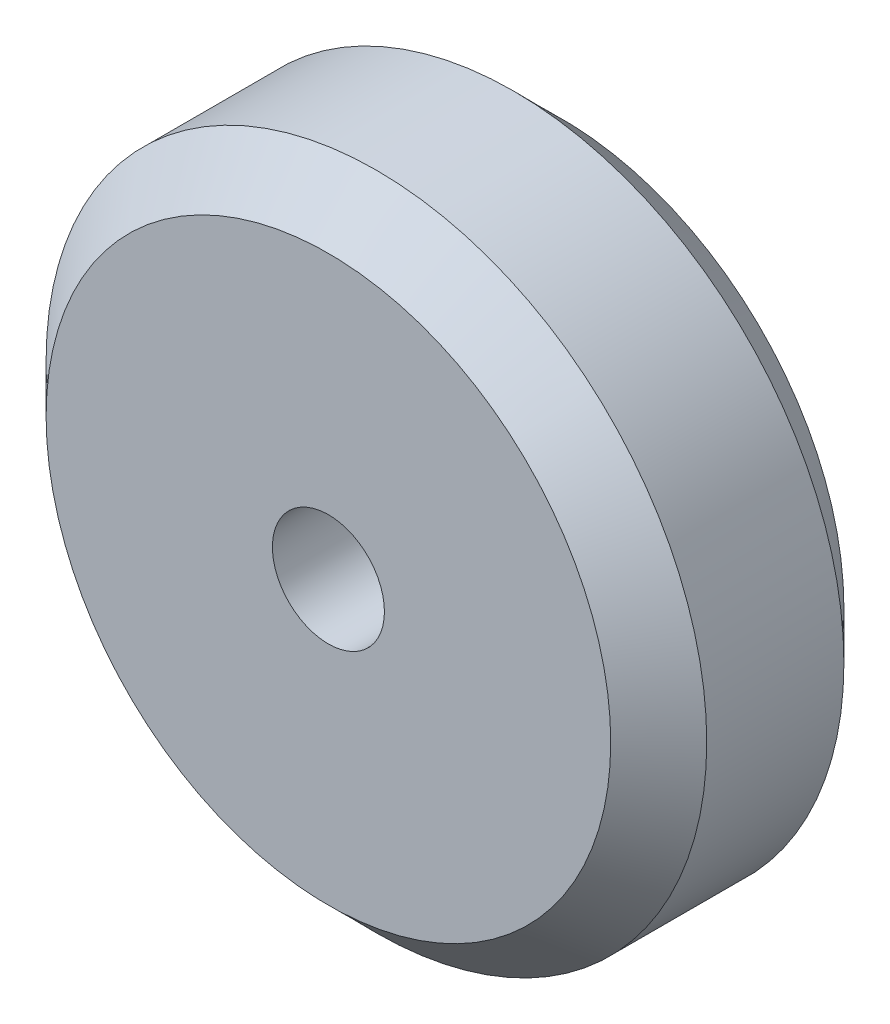
SolidWorks part; units mm, degrees
ref_plane "Front Plane" through (0, 0, 0) normal (0, 0, 1) x (1, 0, 0)
ref_plane "Top Plane" through (0, 0, 0) normal (0, 1, 0) x (1, 0, 0)
ref_plane "Right Plane" through (0, 0, 0) normal (1, 0, 0) x (0, 0, -1)
sketch "Sketch1" plane through (0, 0, 0) normal (1, 0, 0) x (0, 0, -1)
  line L0 (-5.1, 2.45) -> (5.1, 2.45) construction
  line L1 (-5.1, 2.45) -> (-5.1, 12.35)
  line L2 (-5.1, 12.35) -> (-3, 14.45)
  line L3 (-3, 14.45) -> (3, 14.45)
  line L4 (3, 14.45) -> (5.1, 12.35)
  line L5 (5.1, 12.35) -> (5.1, 2.45)
  line L7 (-5.1, 0) -> (5.1, 0) construction
  line L8 (5.1, 0) -> (5.1, 2.45) construction
  line L9 (-5.1, -2.45) -> (-5.1, 2.45) construction
  line L10 (5.1, 2.45) -> (-5.1, 2.45)
  point P4 (0, 0)
  point P19 (-5.1, 0)
  dimension "D1" = 6
  dimension "D2" = 10.2
  dimension "D3" = 24
  dimension "D4" = 135
  dimension "D5" = 4.9
revolve "Revolve1" add sketch "Sketch1" angle 360 about L7
